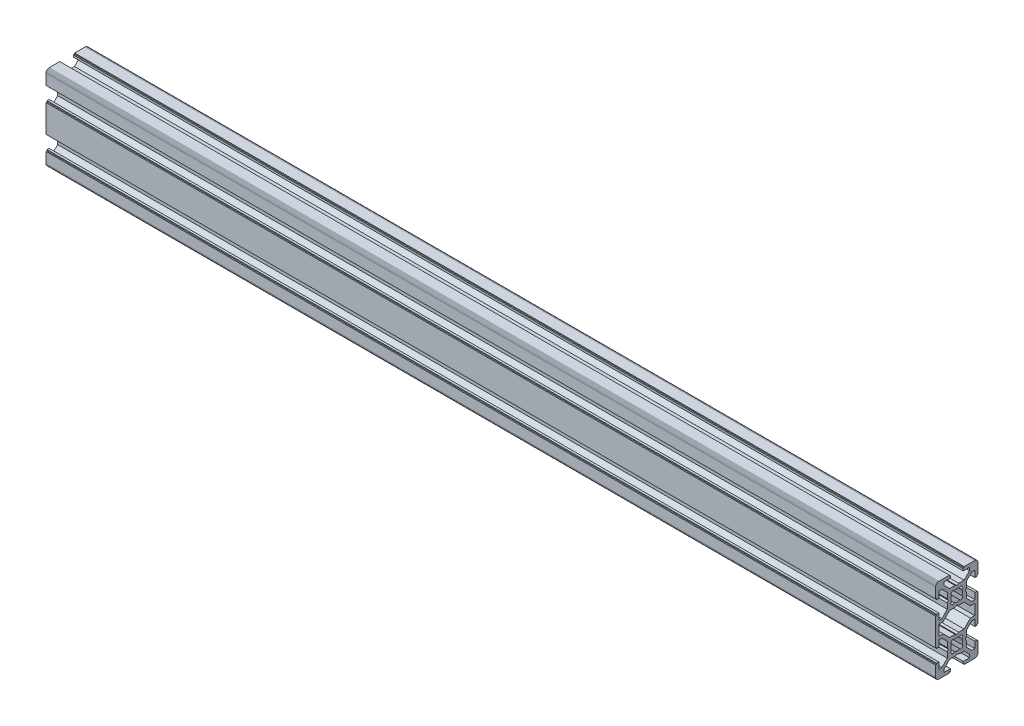
SolidWorks part; units mm, degrees
material "1060 Alloy"
ref_plane "Front Plane" through (0, 0, 0) normal (0, 0, 1) x (1, 0, 0)
ref_plane "Top Plane" through (0, 0, 0) normal (0, 1, 0) x (1, 0, 0)
ref_plane "Right Plane" through (0, 0, 0) normal (1, 0, 0) x (0, 0, -1)
sketch "Sketch1" plane through (0, 0, 0) normal (0, 0, 1) x (1, 0, 0)
  line L0 (0, 0) -> (420, 0)
  dimension "D1" = 420
other "20mm 20X40(1)"
ref_plane "Plane1" through (0, 0, 0) normal (1, 0, 0) x (0, 1, 0)
sketch "Model1" plane through (0, 0, 0) normal (1, 0, 0) x (0, 1, 0)
  line L0 (-19.9985, -8.5673) -> (-20, -8.5)
  line L1 (20, 8.5) -> (19.9985, 8.5673)
  line L2 (-7.2509, 0.0699) -> (-7.258, 0.2095)
  line L3 (-12.742, -0.2095) -> (-12.7491, -0.0699)
  line L4 (12.7491, 0.0699) -> (12.742, 0.2095)
  line L5 (7.2628, -0.2652) -> (7.2514, -0.0885)
  line L6 (-19.994, -8.6345) -> (-19.9985, -8.5673)
  line L7 (19.9985, 8.5673) -> (19.994, 8.6345)
  line L8 (-12.7278, -0.3485) -> (-12.742, -0.2095)
  line L9 (12.742, 0.2095) -> (12.7278, 0.3485)
  line L10 (-7.258, 0.2095) -> (-7.2722, 0.3485)
  line L11 (-19.9864, -8.7013) -> (-19.994, -8.6345)
  line L12 (19.994, 8.6345) -> (19.9864, 8.7013)
  line L13 (7.2855, -0.4407) -> (7.2628, -0.2652)
  line L14 (-12.7066, -0.4866) -> (-12.7278, -0.3485)
  line L15 (12.7278, 0.3485) -> (12.7066, 0.4866)
  line L16 (-7.2722, 0.3485) -> (-7.2934, 0.4866)
  line L17 (-19.9759, -8.7678) -> (-19.9864, -8.7013)
  line L18 (19.9864, 8.7013) -> (19.9759, 8.7678)
  line L19 (7.3195, -0.6144) -> (7.2855, -0.4407)
  line L20 (-19.9624, -8.8338) -> (-19.9759, -8.7678)
  line L21 (19.9759, 8.7678) -> (19.9624, 8.8338)
  line L22 (-12.6784, -0.6235) -> (-12.7066, -0.4866)
  line L23 (12.7066, 0.4866) -> (12.6784, 0.6235)
  line L24 (-7.2934, 0.4866) -> (-7.3216, 0.6235)
  line L25 (-19.9459, -8.8991) -> (-19.9624, -8.8338)
  line L26 (19.9624, 8.8338) -> (19.9459, 8.8991)
  line L27 (-12.6432, -0.7588) -> (-12.6784, -0.6235)
  line L28 (12.6784, 0.6235) -> (12.6432, 0.7588)
  line L29 (-7.3216, 0.6235) -> (-7.3568, 0.7588)
  line L30 (7.3646, -0.7856) -> (7.3195, -0.6144)
  line L31 (-19.9266, -8.9635) -> (-19.9459, -8.8991)
  line L32 (19.9459, 8.8991) -> (19.9266, 8.9635)
  line L33 (-7.3568, 0.7588) -> (-7.3987, 0.8921)
  line L34 (-12.6013, -0.8921) -> (-12.6432, -0.7588)
  line L35 (12.6432, 0.7588) -> (12.6013, 0.8921)
  line L36 (7.4206, -0.9535) -> (7.3646, -0.7856)
  line L37 (-19.9044, -9.0271) -> (-19.9266, -8.9635)
  line L38 (19.9266, 8.9635) -> (19.9044, 9.0271)
  line L39 (-12.5526, -1.0231) -> (-12.6013, -0.8921)
  line L40 (12.6013, 0.8921) -> (12.5526, 1.0231)
  line L41 (-7.3987, 0.8921) -> (-7.4474, 1.0231)
  line L42 (-19.8793, -9.0895) -> (-19.9044, -9.0271)
  line L43 (19.9044, 9.0271) -> (19.8793, 9.0895)
  line L44 (7.4873, -1.1175) -> (7.4206, -0.9535)
  line L45 (-12.4973, -1.1515) -> (-12.5526, -1.0231)
  line L46 (12.5526, 1.0231) -> (12.4973, 1.1515)
  line L47 (-7.4474, 1.0231) -> (-7.5027, 1.1515)
  line L48 (-19.8515, -9.1508) -> (-19.8793, -9.0895)
  line L49 (19.8793, 9.0895) -> (19.8515, 9.1508)
  line L50 (7.5644, -1.2769) -> (7.4873, -1.1175)
  line L51 (-7.5027, 1.1515) -> (-7.5644, 1.2769)
  line L52 (-12.4356, -1.2769) -> (-12.4973, -1.1515)
  line L53 (12.4973, 1.1515) -> (12.4356, 1.2769)
  line L54 (-19.8209, -9.2108) -> (-19.8515, -9.1508)
  line L55 (19.8515, 9.1508) -> (19.8209, 9.2108)
  line L56 (-19.7877, -9.2693) -> (-19.8209, -9.2108)
  line L57 (19.8209, 9.2108) -> (19.7877, 9.2693)
  line L58 (14.5, -0.866) -> (14, 0)
  line L59 (-5.5, -0.866) -> (-6, 0)
  line L60 (-14, 0) -> (-14.5, 0.866)
  line L61 (6, 0) -> (5.5, 0.866)
  line L62 (-19.7519, -9.3263) -> (-19.7877, -9.2693)
  line L63 (19.7877, 9.2693) -> (19.7519, 9.3263)
  line L64 (7.1287, -2.0014) -> (7.0523, -1.8871)
  line L65 (-12.8713, -2.0014) -> (-12.9477, -1.8871)
  line L66 (12.9477, 1.8871) -> (12.8713, 2.0014)
  line L67 (-7.0523, 1.8871) -> (-7.1287, 2.0014)
  line L68 (-19.7135, -9.3817) -> (-19.7519, -9.3263)
  line L69 (19.7519, 9.3263) -> (19.7135, 9.3817)
  line L70 (7.2095, -2.1126) -> (7.1287, -2.0014)
  line L71 (-12.7905, -2.1126) -> (-12.8713, -2.0014)
  line L72 (12.8713, 2.0014) -> (12.7905, 2.1126)
  line L73 (-7.1287, 2.0014) -> (-7.2095, 2.1126)
  line L74 (-19.6727, -9.4352) -> (-19.7135, -9.3817)
  line L75 (19.7135, 9.3817) -> (19.6727, 9.4352)
  line L76 (7.2945, -2.2205) -> (7.2095, -2.1126)
  line L77 (-12.7055, -2.2205) -> (-12.7905, -2.1126)
  line L78 (12.7905, 2.1126) -> (12.7055, 2.2205)
  line L79 (-7.2095, 2.1126) -> (-7.2945, 2.2205)
  line L80 (-19.6296, -9.4869) -> (-19.6727, -9.4352)
  line L81 (19.6727, 9.4352) -> (19.6296, 9.4869)
  line L82 (-7.0523, -1.8871) -> (-7.5644, -1.2769)
  line L83 (7.5644, 1.2769) -> (7.0523, 1.8871)
  line L84 (12.9477, -1.8871) -> (12.4356, -1.2769)
  line L85 (-12.4356, 1.2769) -> (-12.9477, 1.8871)
  line L86 (7.3838, -2.325) -> (7.2945, -2.2205)
  line L87 (-12.6162, -2.325) -> (-12.7055, -2.2205)
  line L88 (12.7055, 2.2205) -> (12.6162, 2.325)
  line L89 (-7.2945, 2.2205) -> (-7.3838, 2.325)
  line L90 (-19.5842, -9.5366) -> (-19.6296, -9.4869)
  line L91 (19.6296, 9.4869) -> (19.5842, 9.5366)
  line L92 (7.4771, -2.4259) -> (7.3838, -2.325)
  line L93 (-7.3838, 2.325) -> (-7.4771, 2.4259)
  line L94 (-12.5229, -2.4259) -> (-12.6162, -2.325)
  line L95 (12.6162, 2.325) -> (12.5229, 2.4259)
  line L96 (-19.5366, -9.5842) -> (-19.5842, -9.5366)
  line L97 (16, -7.0607) -> (13.4393, -4.5)
  line L98 (-14.5, 3.4393) -> (-17.0607, 6)
  line L99 (-4, -7.0607) -> (-6.5607, -4.5)
  line L100 (5.5, 3.4393) -> (2.5, 6.4393)
  line L101 (6.5607, 4.5) -> (4, 7.0607)
  line L102 (17.0607, -6) -> (14.5, -3.4393)
  line L103 (-13.4393, 4.5) -> (-16, 7.0607)
  line L104 (-2.5, -6.4393) -> (-5.5, -3.4393)
  line L105 (19.5842, 9.5366) -> (19.5366, 9.5842)
  line L106 (-12.4258, -2.523) -> (-12.5229, -2.4259)
  line L107 (12.5229, 2.4259) -> (12.4258, 2.523)
  line L108 (7.5742, -2.523) -> (7.4771, -2.4259)
  line L109 (-7.4771, 2.4259) -> (-7.5742, 2.523)
  line L110 (7.6752, -2.6163) -> (7.5742, -2.523)
  line L111 (-7.5742, 2.523) -> (-7.6752, 2.6163)
  line L112 (-12.3248, -2.6163) -> (-12.4258, -2.523)
  line L113 (12.4258, 2.523) -> (12.3248, 2.6163)
  line L114 (-19.4869, -9.6296) -> (-19.5366, -9.5842)
  line L115 (19.5366, 9.5842) -> (19.4869, 9.6296)
  line L116 (-12.2203, -2.7056) -> (-12.3248, -2.6163)
  line L117 (12.3248, 2.6163) -> (12.2203, 2.7056)
  line L118 (7.7797, -2.7056) -> (7.6752, -2.6163)
  line L119 (-7.6752, 2.6163) -> (-7.7797, 2.7056)
  line L120 (11.887, -2.9478) -> (11.2767, -2.4357)
  line L121 (-8.113, -2.9478) -> (-8.7233, -2.4357)
  line L122 (8.7233, 2.4357) -> (8.113, 2.9478)
  line L123 (-11.2767, 2.4357) -> (-11.887, 2.9478)
  line L124 (-19.4352, -9.6727) -> (-19.4869, -9.6296)
  line L125 (19.4869, 9.6296) -> (19.4352, 9.6727)
  line L126 (7.8876, -2.7906) -> (7.7797, -2.7056)
  line L127 (-12.1124, -2.7906) -> (-12.2203, -2.7056)
  line L128 (12.2203, 2.7056) -> (12.1124, 2.7906)
  line L129 (-7.7797, 2.7056) -> (-7.8876, 2.7906)
  line L130 (-19.3817, -9.7135) -> (-19.4352, -9.6727)
  line L131 (19.4352, 9.6727) -> (19.3817, 9.7135)
  line L132 (7.9987, -2.8714) -> (7.8876, -2.7906)
  line L133 (-7.8876, 2.7906) -> (-7.9987, 2.8714)
  line L134 (-12.0012, -2.8714) -> (-12.1124, -2.7906)
  line L135 (12.1124, 2.7906) -> (12.0012, 2.8714)
  line L136 (-19.3263, -9.7519) -> (-19.3817, -9.7135)
  line L137 (19.3817, 9.7135) -> (19.3263, 9.7519)
  line L138 (-11.887, -2.9478) -> (-12.0012, -2.8714)
  line L139 (12.0012, 2.8714) -> (11.887, 2.9478)
  line L140 (8.113, -2.9478) -> (7.9987, -2.8714)
  line L141 (-7.9987, 2.8714) -> (-8.113, 2.9478)
  line L142 (-19.2693, -9.7877) -> (-19.3263, -9.7519)
  line L143 (19.3263, 9.7519) -> (19.2693, 9.7877)
  line L144 (-9.134, -4.5) -> (-10, -4)
  line L145 (10.866, -4.5) -> (10, -4)
  line L146 (10, 4) -> (9.134, 4.5)
  line L147 (-10, 4) -> (-10.866, 4.5)
  line L148 (-19.2108, -9.8209) -> (-19.2693, -9.7877)
  line L149 (19.2693, 9.7877) -> (19.2108, 9.8209)
  line L150 (-19.1508, -9.8515) -> (-19.2108, -9.8209)
  line L151 (19.2108, 9.8209) -> (19.1508, 9.8515)
  line L152 (8.8487, -2.4974) -> (8.7233, -2.4357)
  line L153 (-11.1513, -2.4974) -> (-11.2767, -2.4357)
  line L154 (11.2767, 2.4357) -> (11.1513, 2.4974)
  line L155 (-8.7233, 2.4357) -> (-8.8487, 2.4974)
  line L156 (-19.0895, -9.8793) -> (-19.1508, -9.8515)
  line L157 (19.1508, 9.8515) -> (19.0895, 9.8793)
  line L158 (8.977, -2.5526) -> (8.8487, -2.4974)
  line L159 (-11.023, -2.5526) -> (-11.1513, -2.4974)
  line L160 (11.1513, 2.4974) -> (11.023, 2.5526)
  line L161 (-8.8487, 2.4974) -> (-8.977, 2.5526)
  line L162 (-19.0271, -9.9044) -> (-19.0895, -9.8793)
  line L163 (19.0895, 9.8793) -> (19.0271, 9.9044)
  line L164 (9.108, -2.6013) -> (8.977, -2.5526)
  line L165 (-10.892, -2.6013) -> (-11.023, -2.5526)
  line L166 (11.023, 2.5526) -> (10.892, 2.6013)
  line L167 (-8.977, 2.5526) -> (-9.108, 2.6013)
  line L168 (-18.9635, -9.9266) -> (-19.0271, -9.9044)
  line L169 (19.0271, 9.9044) -> (18.9635, 9.9266)
  line L170 (9.2413, -2.6433) -> (9.108, -2.6013)
  line L171 (-10.7587, -2.6433) -> (-10.892, -2.6013)
  line L172 (10.892, 2.6013) -> (10.7587, 2.6433)
  line L173 (-9.108, 2.6013) -> (-9.2413, 2.6433)
  line L174 (-18.8991, -9.9459) -> (-18.9635, -9.9266)
  line L175 (18.9635, 9.9266) -> (18.8991, 9.9459)
  line L176 (9.3766, -2.6784) -> (9.2413, -2.6433)
  line L177 (-10.6234, -2.6784) -> (-10.7587, -2.6433)
  line L178 (10.7587, 2.6433) -> (10.6234, 2.6784)
  line L179 (-9.2413, 2.6433) -> (-9.3766, 2.6784)
  line L180 (-18.8338, -9.9624) -> (-18.8991, -9.9459)
  line L181 (18.8991, 9.9459) -> (18.8338, 9.9624)
  line L182 (9.5134, -2.7066) -> (9.3766, -2.6784)
  line L183 (-10.4866, -2.7066) -> (-10.6234, -2.6784)
  line L184 (10.6234, 2.6784) -> (10.4866, 2.7066)
  line L185 (-9.3766, 2.6784) -> (-9.5134, 2.7066)
  line L186 (-18.7678, -9.9759) -> (-18.8338, -9.9624)
  line L187 (18.8338, 9.9624) -> (18.7678, 9.9759)
  line L188 (-18.7013, -9.9864) -> (-18.7678, -9.9759)
  line L189 (18.7678, 9.9759) -> (18.7013, 9.9864)
  line L190 (9.6515, -2.7278) -> (9.5134, -2.7066)
  line L191 (-10.3485, -2.7278) -> (-10.4866, -2.7066)
  line L192 (10.4866, 2.7066) -> (10.3485, 2.7278)
  line L193 (-9.5134, 2.7066) -> (-9.6515, 2.7278)
  line L194 (-18.6345, -9.994) -> (-18.7013, -9.9864)
  line L195 (18.7013, 9.9864) -> (18.6345, 9.994)
  line L196 (9.7906, -2.742) -> (9.6515, -2.7278)
  line L197 (-10.2094, -2.742) -> (-10.3485, -2.7278)
  line L198 (10.3485, 2.7278) -> (10.2094, 2.742)
  line L199 (-9.6515, 2.7278) -> (-9.7906, 2.742)
  line L200 (-18.5673, -9.9985) -> (-18.6345, -9.994)
  line L201 (18.6345, 9.994) -> (18.5673, 9.9985)
  line L202 (9.9301, -2.7491) -> (9.7906, -2.742)
  line L203 (-10.0699, -2.7491) -> (-10.2094, -2.742)
  line L204 (10.2094, 2.742) -> (10.0699, 2.7491)
  line L205 (-9.7906, 2.742) -> (-9.9301, 2.7491)
  line L206 (-18.5, -10) -> (-18.5673, -9.9985)
  line L207 (18.5673, 9.9985) -> (18.5, 10)
  line L208 (-18.5, -10) -> (-13.5, -10)
  line L209 (-6.5, -10) -> (6.5, -10)
  line L210 (13.5, -10) -> (18.5, -10)
  line L211 (-13.5, -9.5) -> (-13, -9.5)
  line L212 (-7, -9.5) -> (-6.5, -9.5)
  line L213 (6.5, -9.5) -> (7, -9.5)
  line L214 (13, -9.5) -> (13.5, -9.5)
  line L215 (-16, -8.5) -> (-13, -8.5)
  line L216 (-7, -8.5) -> (-4, -8.5)
  line L217 (4, -8.5) -> (7, -8.5)
  line L218 (13, -8.5) -> (16, -8.5)
  line L219 (-2.5, -8.5) -> (2.5, -8.5)
  line L220 (-18.5, -6) -> (-17.0607, -6)
  line L221 (17.0607, -6) -> (18.5, -6)
  line L222 (-13.4393, -4.5) -> (-10.866, -4.5)
  line L223 (-9.134, -4.5) -> (-6.5607, -4.5)
  line L224 (6.5607, -4.5) -> (9.134, -4.5)
  line L225 (10.866, -4.5) -> (13.4393, -4.5)
  line L226 (-20, -3.5) -> (-19.5, -3.5)
  line L227 (19.5, -3.5) -> (20, -3.5)
  line L228 (-19.5, -3) -> (-18.5, -3)
  line L229 (18.5, -3) -> (19.5, -3)
  line L230 (9.9301, -2.7491) -> (10.0699, -2.7491)
  line L231 (-10.0699, -2.7491) -> (-9.9301, -2.7491)
  line L232 (9.9301, 2.7491) -> (10.0699, 2.7491)
  line L233 (-10.0699, 2.7491) -> (-9.9301, 2.7491)
  line L234 (-19.5, 3) -> (-18.5, 3)
  line L235 (18.5, 3) -> (19.5, 3)
  line L236 (-20, 3.5) -> (-19.5, 3.5)
  line L237 (19.5, 3.5) -> (20, 3.5)
  line L238 (6.5607, 4.5) -> (9.134, 4.5)
  line L239 (-9.134, 4.5) -> (-6.5607, 4.5)
  line L240 (-13.4393, 4.5) -> (-10.866, 4.5)
  line L241 (10.866, 4.5) -> (13.4393, 4.5)
  line L242 (-18.5, 6) -> (-17.0607, 6)
  line L243 (17.0607, 6) -> (18.5, 6)
  line L244 (4, 8.5) -> (7, 8.5)
  line L245 (-7, 8.5) -> (-4, 8.5)
  line L246 (-16, 8.5) -> (-13, 8.5)
  line L247 (13, 8.5) -> (16, 8.5)
  line L248 (-2.5, 8.5) -> (2.5, 8.5)
  line L249 (6.5, 9.5) -> (7, 9.5)
  line L250 (-7, 9.5) -> (-6.5, 9.5)
  line L251 (-13.5, 9.5) -> (-13, 9.5)
  line L252 (13, 9.5) -> (13.5, 9.5)
  line L253 (-6.5, 10) -> (6.5, 10)
  line L254 (-18.5, 10) -> (-13.5, 10)
  line L255 (13.5, 10) -> (18.5, 10)
  line L256 (18.5, -10) -> (18.5673, -9.9985)
  line L257 (-18.5673, 9.9985) -> (-18.5, 10)
  line L258 (10.0699, -2.7491) -> (10.2094, -2.742)
  line L259 (-9.9301, -2.7491) -> (-9.7906, -2.742)
  line L260 (9.7906, 2.742) -> (9.9301, 2.7491)
  line L261 (-10.2094, 2.742) -> (-10.0699, 2.7491)
  line L262 (18.5673, -9.9985) -> (18.6345, -9.994)
  line L263 (-18.6345, 9.994) -> (-18.5673, 9.9985)
  line L264 (10.2094, -2.742) -> (10.3485, -2.7278)
  line L265 (-9.7906, -2.742) -> (-9.6515, -2.7278)
  line L266 (9.6515, 2.7278) -> (9.7906, 2.742)
  line L267 (-10.3485, 2.7278) -> (-10.2094, 2.742)
  line L268 (18.6345, -9.994) -> (18.7013, -9.9864)
  line L269 (-18.7013, 9.9864) -> (-18.6345, 9.994)
  line L270 (10.3485, -2.7278) -> (10.4866, -2.7066)
  line L271 (-9.6515, -2.7278) -> (-9.5134, -2.7066)
  line L272 (9.5134, 2.7066) -> (9.6515, 2.7278)
  line L273 (-10.4866, 2.7066) -> (-10.3485, 2.7278)
  line L274 (18.7013, -9.9864) -> (18.7678, -9.9759)
  line L275 (-18.7678, 9.9759) -> (-18.7013, 9.9864)
  line L276 (18.7678, -9.9759) -> (18.8338, -9.9624)
  line L277 (-18.8338, 9.9624) -> (-18.7678, 9.9759)
  line L278 (10.4866, -2.7066) -> (10.6234, -2.6784)
  line L279 (-9.5134, -2.7066) -> (-9.3766, -2.6784)
  line L280 (9.3766, 2.6784) -> (9.5134, 2.7066)
  line L281 (-10.6234, 2.6784) -> (-10.4866, 2.7066)
  line L282 (18.8338, -9.9624) -> (18.8991, -9.9459)
  line L283 (-18.8991, 9.9459) -> (-18.8338, 9.9624)
  line L284 (10.6234, -2.6784) -> (10.7587, -2.6433)
  line L285 (-9.3766, -2.6784) -> (-9.2413, -2.6433)
  line L286 (9.2413, 2.6433) -> (9.3766, 2.6784)
  line L287 (-10.7587, 2.6433) -> (-10.6234, 2.6784)
  line L288 (18.8991, -9.9459) -> (18.9635, -9.9266)
  line L289 (-18.9635, 9.9266) -> (-18.8991, 9.9459)
  line L290 (10.7587, -2.6433) -> (10.892, -2.6013)
  line L291 (-9.2413, -2.6433) -> (-9.108, -2.6013)
  line L292 (9.108, 2.6013) -> (9.2413, 2.6433)
  line L293 (-10.892, 2.6013) -> (-10.7587, 2.6433)
  line L294 (18.9635, -9.9266) -> (19.0271, -9.9044)
  line L295 (-19.0271, 9.9044) -> (-18.9635, 9.9266)
  line L296 (10.892, -2.6013) -> (11.023, -2.5526)
  line L297 (-9.108, -2.6013) -> (-8.977, -2.5526)
  line L298 (8.977, 2.5526) -> (9.108, 2.6013)
  line L299 (-11.023, 2.5526) -> (-10.892, 2.6013)
  line L300 (19.0271, -9.9044) -> (19.0895, -9.8793)
  line L301 (-19.0895, 9.8793) -> (-19.0271, 9.9044)
  line L302 (11.023, -2.5526) -> (11.1513, -2.4974)
  line L303 (-8.977, -2.5526) -> (-8.8487, -2.4974)
  line L304 (8.8487, 2.4974) -> (8.977, 2.5526)
  line L305 (-11.1513, 2.4974) -> (-11.023, 2.5526)
  line L306 (19.0895, -9.8793) -> (19.1508, -9.8515)
  line L307 (-19.1508, 9.8515) -> (-19.0895, 9.8793)
  line L308 (11.1513, -2.4974) -> (11.2767, -2.4357)
  line L309 (-8.8487, -2.4974) -> (-8.7233, -2.4357)
  line L310 (8.7233, 2.4357) -> (8.8487, 2.4974)
  line L311 (-11.2767, 2.4357) -> (-11.1513, 2.4974)
  line L312 (19.1508, -9.8515) -> (19.2108, -9.8209)
  line L313 (-19.2108, 9.8209) -> (-19.1508, 9.8515)
  line L314 (19.2108, -9.8209) -> (19.2693, -9.7877)
  line L315 (-19.2693, 9.7877) -> (-19.2108, 9.8209)
  line L316 (-10.866, -4.5) -> (-10, -4)
  line L317 (9.134, -4.5) -> (10, -4)
  line L318 (-10, 4) -> (-9.134, 4.5)
  line L319 (10, 4) -> (10.866, 4.5)
  line L320 (19.2693, -9.7877) -> (19.3263, -9.7519)
  line L321 (-19.3263, 9.7519) -> (-19.2693, 9.7877)
  line L322 (-8.113, -2.9478) -> (-7.9987, -2.8714)
  line L323 (7.9987, 2.8714) -> (8.113, 2.9478)
  line L324 (11.887, -2.9478) -> (12.0012, -2.8714)
  line L325 (-12.0012, 2.8714) -> (-11.887, 2.9478)
  line L326 (19.3263, -9.7519) -> (19.3817, -9.7135)
  line L327 (-19.3817, 9.7135) -> (-19.3263, 9.7519)
  line L328 (12.0012, -2.8714) -> (12.1124, -2.7906)
  line L329 (-12.1124, 2.7906) -> (-12.0012, 2.8714)
  line L330 (-7.9987, -2.8714) -> (-7.8876, -2.7906)
  line L331 (7.8876, 2.7906) -> (7.9987, 2.8714)
  line L332 (19.3817, -9.7135) -> (19.4352, -9.6727)
  line L333 (-19.4352, 9.6727) -> (-19.3817, 9.7135)
  line L334 (12.1124, -2.7906) -> (12.2203, -2.7056)
  line L335 (-7.8876, -2.7906) -> (-7.7797, -2.7056)
  line L336 (7.7797, 2.7056) -> (7.8876, 2.7906)
  line L337 (-12.2203, 2.7056) -> (-12.1124, 2.7906)
  line L338 (19.4352, -9.6727) -> (19.4869, -9.6296)
  line L339 (-19.4869, 9.6296) -> (-19.4352, 9.6727)
  line L340 (8.113, -2.9478) -> (8.7233, -2.4357)
  line L341 (-11.887, -2.9478) -> (-11.2767, -2.4357)
  line L342 (11.2767, 2.4357) -> (11.887, 2.9478)
  line L343 (-8.7233, 2.4357) -> (-8.113, 2.9478)
  line L344 (-7.7797, -2.7056) -> (-7.6752, -2.6163)
  line L345 (7.6752, 2.6163) -> (7.7797, 2.7056)
  line L346 (12.2203, -2.7056) -> (12.3248, -2.6163)
  line L347 (-12.3248, 2.6163) -> (-12.2203, 2.7056)
  line L348 (19.4869, -9.6296) -> (19.5366, -9.5842)
  line L349 (-19.5366, 9.5842) -> (-19.4869, 9.6296)
  line L350 (12.3248, -2.6163) -> (12.4258, -2.523)
  line L351 (-12.4258, 2.523) -> (-12.3248, 2.6163)
  line L352 (-7.6752, -2.6163) -> (-7.5742, -2.523)
  line L353 (7.5742, 2.523) -> (7.6752, 2.6163)
  line L354 (-7.5742, -2.523) -> (-7.4771, -2.4259)
  line L355 (7.4771, 2.4259) -> (7.5742, 2.523)
  line L356 (12.4258, -2.523) -> (12.5229, -2.4259)
  line L357 (-12.5229, 2.4259) -> (-12.4258, 2.523)
  line L358 (19.5366, -9.5842) -> (19.5842, -9.5366)
  line L359 (-16, -7.0607) -> (-13.4393, -4.5)
  line L360 (4, -7.0607) -> (6.5607, -4.5)
  line L361 (2.5, -6.4393) -> (5.5, -3.4393)
  line L362 (14.5, 3.4393) -> (17.0607, 6)
  line L363 (-5.5, 3.4393) -> (-2.5, 6.4393)
  line L364 (-6.5607, 4.5) -> (-4, 7.0607)
  line L365 (-17.0607, -6) -> (-14.5, -3.4393)
  line L366 (13.4393, 4.5) -> (16, 7.0607)
  line L367 (-19.5842, 9.5366) -> (-19.5366, 9.5842)
  line L368 (12.5229, -2.4259) -> (12.6162, -2.325)
  line L369 (-12.6162, 2.325) -> (-12.5229, 2.4259)
  line L370 (-7.4771, -2.4259) -> (-7.3838, -2.325)
  line L371 (7.3838, 2.325) -> (7.4771, 2.4259)
  line L372 (19.5842, -9.5366) -> (19.6296, -9.4869)
  line L373 (-19.6296, 9.4869) -> (-19.5842, 9.5366)
  line L374 (12.6162, -2.325) -> (12.7055, -2.2205)
  line L375 (-7.3838, -2.325) -> (-7.2945, -2.2205)
  line L376 (7.2945, 2.2205) -> (7.3838, 2.325)
  line L377 (-12.7055, 2.2205) -> (-12.6162, 2.325)
  line L378 (-12.9477, -1.8871) -> (-12.4356, -1.2769)
  line L379 (12.4356, 1.2769) -> (12.9477, 1.8871)
  line L380 (7.0523, -1.8871) -> (7.5644, -1.2769)
  line L381 (-7.5644, 1.2769) -> (-7.0523, 1.8871)
  line L382 (19.6296, -9.4869) -> (19.6727, -9.4352)
  line L383 (-19.6727, 9.4352) -> (-19.6296, 9.4869)
  line L384 (12.7055, -2.2205) -> (12.7905, -2.1126)
  line L385 (-7.2945, -2.2205) -> (-7.2095, -2.1126)
  line L386 (7.2095, 2.1126) -> (7.2945, 2.2205)
  line L387 (-12.7905, 2.1126) -> (-12.7055, 2.2205)
  line L388 (19.6727, -9.4352) -> (19.7135, -9.3817)
  line L389 (-19.7135, 9.3817) -> (-19.6727, 9.4352)
  line L390 (12.7905, -2.1126) -> (12.8713, -2.0014)
  line L391 (-7.2095, -2.1126) -> (-7.1287, -2.0014)
  line L392 (7.1287, 2.0014) -> (7.2095, 2.1126)
  line L393 (-12.8713, 2.0014) -> (-12.7905, 2.1126)
  line L394 (19.7135, -9.3817) -> (19.7519, -9.3263)
  line L395 (-19.7519, 9.3263) -> (-19.7135, 9.3817)
  line L396 (12.8713, -2.0014) -> (12.9477, -1.8871)
  line L397 (-7.1287, -2.0014) -> (-7.0523, -1.8871)
  line L398 (7.0523, 1.8871) -> (7.1287, 2.0014)
  line L399 (-12.9477, 1.8871) -> (-12.8713, 2.0014)
  line L400 (19.7519, -9.3263) -> (19.7877, -9.2693)
  line L401 (-19.7877, 9.2693) -> (-19.7519, 9.3263)
  line L402 (-14.5, -0.866) -> (-14, 0)
  line L403 (5.5, -0.866) -> (6, 0)
  line L404 (14, 0) -> (14.5, 0.866)
  line L405 (-6, 0) -> (-5.5, 0.866)
  line L406 (19.7877, -9.2693) -> (19.8209, -9.2108)
  line L407 (-19.8209, 9.2108) -> (-19.7877, 9.2693)
  line L408 (19.8209, -9.2108) -> (19.8515, -9.1508)
  line L409 (-19.8515, 9.1508) -> (-19.8209, 9.2108)
  line L410 (12.4356, -1.2769) -> (12.4973, -1.1515)
  line L411 (-12.4973, 1.1515) -> (-12.4356, 1.2769)
  line L412 (-7.5644, -1.2769) -> (-7.5027, -1.1515)
  line L413 (7.4873, 1.1175) -> (7.5644, 1.2769)
  line L414 (19.8515, -9.1508) -> (19.8793, -9.0895)
  line L415 (-19.8793, 9.0895) -> (-19.8515, 9.1508)
  line L416 (12.4973, -1.1515) -> (12.5526, -1.0231)
  line L417 (-7.5027, -1.1515) -> (-7.4474, -1.0231)
  line L418 (-12.5526, 1.0231) -> (-12.4973, 1.1515)
  line L419 (7.4206, 0.9535) -> (7.4873, 1.1175)
  line L420 (19.8793, -9.0895) -> (19.9044, -9.0271)
  line L421 (-19.9044, 9.0271) -> (-19.8793, 9.0895)
  line L422 (12.5526, -1.0231) -> (12.6013, -0.8921)
  line L423 (-7.4474, -1.0231) -> (-7.3987, -0.8921)
  line L424 (-12.6013, 0.8921) -> (-12.5526, 1.0231)
  line L425 (19.9044, -9.0271) -> (19.9266, -8.9635)
  line L426 (-19.9266, 8.9635) -> (-19.9044, 9.0271)
  line L427 (7.3646, 0.7856) -> (7.4206, 0.9535)
  line L428 (12.6013, -0.8921) -> (12.6432, -0.7588)
  line L429 (-12.6432, 0.7588) -> (-12.6013, 0.8921)
  line L430 (-7.3987, -0.8921) -> (-7.3568, -0.7588)
  line L431 (19.9266, -8.9635) -> (19.9459, -8.8991)
  line L432 (-19.9459, 8.8991) -> (-19.9266, 8.9635)
  line L433 (7.3195, 0.6144) -> (7.3646, 0.7856)
  line L434 (-7.3568, -0.7588) -> (-7.3216, -0.6235)
  line L435 (12.6432, -0.7588) -> (12.6784, -0.6235)
  line L436 (-12.6784, 0.6235) -> (-12.6432, 0.7588)
  line L437 (19.9459, -8.8991) -> (19.9624, -8.8338)
  line L438 (-19.9624, 8.8338) -> (-19.9459, 8.8991)
  line L439 (12.6784, -0.6235) -> (12.7066, -0.4866)
  line L440 (-7.3216, -0.6235) -> (-7.2934, -0.4866)
  line L441 (-12.7066, 0.4866) -> (-12.6784, 0.6235)
  line L442 (19.9624, -8.8338) -> (19.9759, -8.7678)
  line L443 (-19.9759, 8.7678) -> (-19.9624, 8.8338)
  line L444 (7.2855, 0.4407) -> (7.3195, 0.6144)
  line L445 (19.9759, -8.7678) -> (19.9864, -8.7013)
  line L446 (-19.9864, 8.7013) -> (-19.9759, 8.7678)
  line L447 (12.7066, -0.4866) -> (12.7278, -0.3485)
  line L448 (-7.2934, -0.4866) -> (-7.2722, -0.3485)
  line L449 (-12.7278, 0.3485) -> (-12.7066, 0.4866)
  line L450 (7.2628, 0.2652) -> (7.2855, 0.4407)
  line L451 (19.9864, -8.7013) -> (19.994, -8.6345)
  line L452 (-19.994, 8.6345) -> (-19.9864, 8.7013)
  line L453 (-7.2722, -0.3485) -> (-7.258, -0.2095)
  line L454 (12.7278, -0.3485) -> (12.742, -0.2095)
  line L455 (-12.742, 0.2095) -> (-12.7278, 0.3485)
  line L456 (19.994, -8.6345) -> (19.9985, -8.5673)
  line L457 (-19.9985, 8.5673) -> (-19.994, 8.6345)
  line L458 (7.2514, 0.0885) -> (7.2628, 0.2652)
  line L459 (12.742, -0.2095) -> (12.7491, -0.0699)
  line L460 (-12.7491, 0.0699) -> (-12.742, 0.2095)
  line L461 (-7.258, -0.2095) -> (-7.2509, -0.0699)
  line L462 (19.9985, -8.5673) -> (20, -8.5)
  line L463 (-20, 8.5) -> (-19.9985, 8.5673)
  line L464 (-20, 3.5) -> (-20, 8.5)
  line L465 (-20, -8.5) -> (-20, -3.5)
  line L466 (-19.5, 3) -> (-19.5, 3.5)
  line L467 (-19.5, -3.5) -> (-19.5, -3)
  line L468 (-18.5, 3) -> (-18.5, 6)
  line L469 (-18.5, -6) -> (-18.5, -3)
  line L470 (-16, 7.0607) -> (-16, 8.5)
  line L471 (-16, -8.5) -> (-16, -7.0607)
  line L472 (-14.5, 0.866) -> (-14.5, 3.4393)
  line L473 (-14.5, -3.4393) -> (-14.5, -0.866)
  line L474 (-13.5, 9.5) -> (-13.5, 10)
  line L475 (-13.5, -10) -> (-13.5, -9.5)
  line L476 (-13, 8.5) -> (-13, 9.5)
  line L477 (-13, -9.5) -> (-13, -8.5)
  line L478 (-12.7491, -0.0699) -> (-12.7491, 0.0699)
  line L479 (-7.2509, -0.0699) -> (-7.2509, 0.0699)
  line L480 (-7, 8.5) -> (-7, 9.5)
  line L481 (-7, -9.5) -> (-7, -8.5)
  line L482 (-6.5, 9.5) -> (-6.5, 10)
  line L483 (-6.5, -10) -> (-6.5, -9.5)
  line L484 (-5.5, -3.4393) -> (-5.5, -0.866)
  line L485 (-5.5, 0.866) -> (-5.5, 3.4393)
  line L486 (-4, 7.0607) -> (-4, 8.5)
  line L487 (-4, -8.5) -> (-4, -7.0607)
  line L488 (-2.5, -8.5) -> (-2.5, -6.4393)
  line L489 (-2.5, 6.4393) -> (-2.5, 8.5)
  line L490 (2.5, -8.5) -> (2.5, -6.4393)
  line L491 (2.5, 6.4393) -> (2.5, 8.5)
  line L492 (4, 7.0607) -> (4, 8.5)
  line L493 (4, -8.5) -> (4, -7.0607)
  line L494 (5.5, -3.4393) -> (5.5, -0.866)
  line L495 (5.5, 0.866) -> (5.5, 3.4393)
  line L496 (6.5, 9.5) -> (6.5, 10)
  line L497 (6.5, -10) -> (6.5, -9.5)
  line L498 (7, 8.5) -> (7, 9.5)
  line L499 (7, -9.5) -> (7, -8.5)
  line L500 (7.2514, -0.0885) -> (7.2514, 0.0885)
  line L501 (12.7491, -0.0699) -> (12.7491, 0.0699)
  line L502 (13, -9.5) -> (13, -8.5)
  line L503 (13, 8.5) -> (13, 9.5)
  line L504 (13.5, -10) -> (13.5, -9.5)
  line L505 (13.5, 9.5) -> (13.5, 10)
  line L506 (14.5, -3.4393) -> (14.5, -0.866)
  line L507 (14.5, 0.866) -> (14.5, 3.4393)
  line L508 (16, -8.5) -> (16, -7.0607)
  line L509 (16, 7.0607) -> (16, 8.5)
  line L510 (18.5, -6) -> (18.5, -3)
  line L511 (18.5, 3) -> (18.5, 6)
  line L512 (19.5, -3.5) -> (19.5, -3)
  line L513 (19.5, 3) -> (19.5, 3.5)
  line L514 (20, -8.5) -> (20, -3.5)
  line L515 (20, 3.5) -> (20, 8.5)
  point P516 (0, 0)
